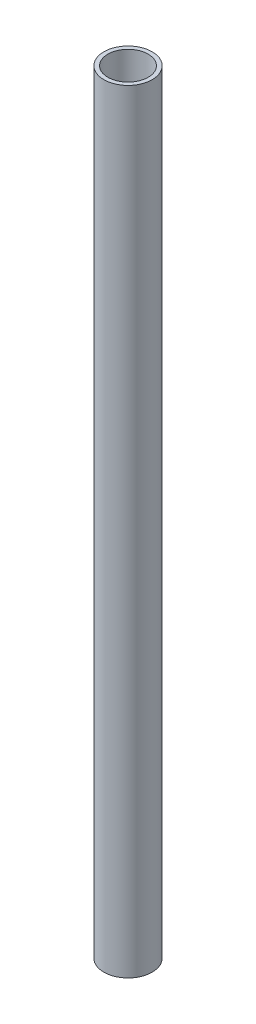
SolidWorks part; units mm, degrees
material "6061-T6 (SS)"
ref_plane "Front Plane" through (0, 0, 0) normal (0, 0, 1) x (1, 0, 0)
ref_plane "Top Plane" through (0, 0, 0) normal (0, 1, 0) x (1, 0, 0)
ref_plane "Right Plane" through (0, 0, 0) normal (1, 0, 0) x (0, 0, -1)
sketch "Sketch1" plane through (0, 0, 0) normal (0, 1, 0) x (1, 0, 0)
  circle A0 centre (0, 0) radius 7.9375
  circle A1 centre (0, 0) radius 9.525
  dimension "D1" = 19.05
  dimension "D2" = 15.875
extrude "Boss-Extrude1" add sketch "Sketch1" along normal blind 304.8
